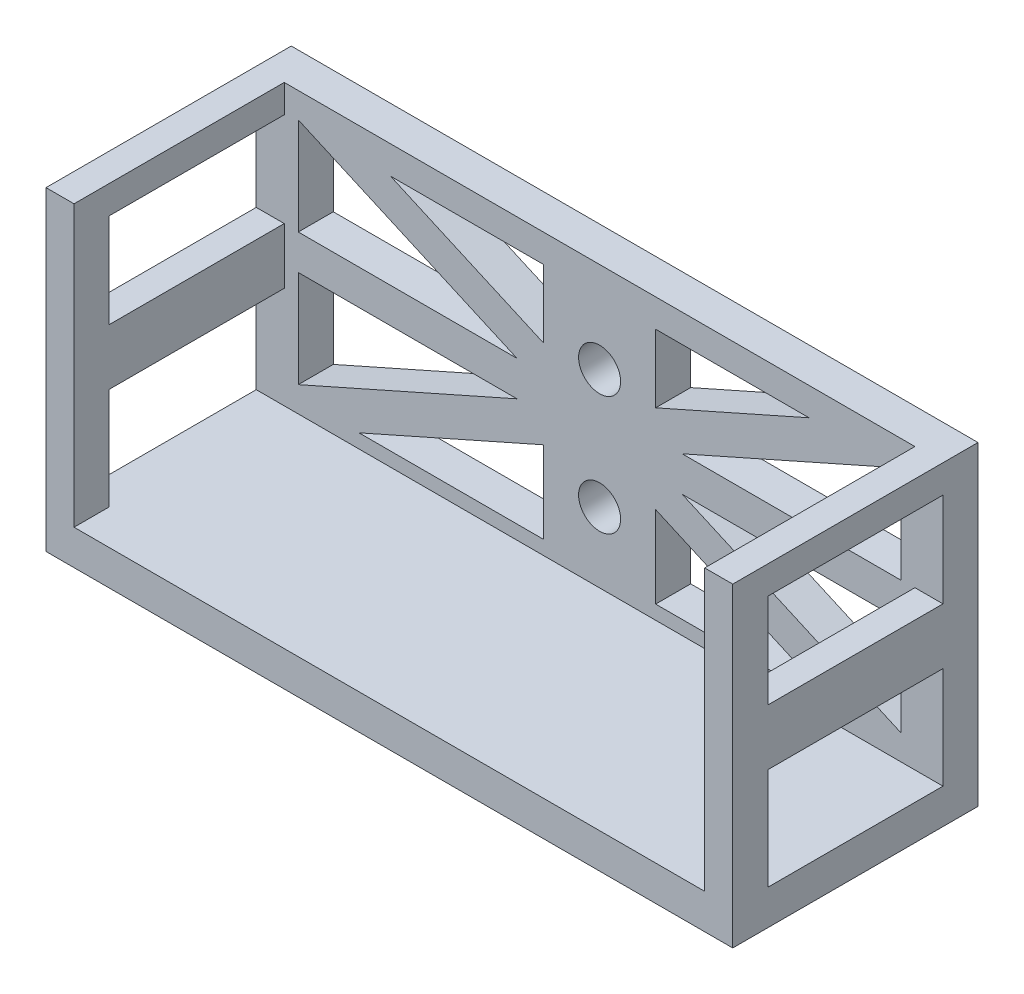
SolidWorks part; units mm, degrees
material "6061-T6 (SS)"
ref_plane "Front Plane" through (0, 0, 0) normal (0, 0, 1) x (1, 0, 0)
ref_plane "Top Plane" through (0, 0, 0) normal (0, 1, 0) x (1, 0, 0)
ref_plane "Right Plane" through (0, 0, 0) normal (1, 0, 0) x (0, 0, -1)
sketch "Sketch1" plane through (0, 0, 0) normal (0, 0, 1) x (1, 0, 0)
  line L1 (-45, 20) -> (45, 20)
  line L2 (-45, 20) -> (-45, -20)
  line L3 (-45, -20) -> (45, -20)
  line L4 (45, 20) -> (45, -20)
  line L5 (-45, 20) -> (45, -20) construction
  line L6 (-45, -20) -> (45, 20) construction
  point P0 (0, 0)
  dimension "D1" = 40
  dimension "D2" = 90
extrude "Boss-Extrude1" add sketch "Sketch1" along normal blind 5
sketch "Sketch2" plane through (0, 0, 0) normal (0, 0, 1) x (1, 0, 0)
  line L1 (-45, 20) -> (-49, 20)
  line L2 (-45, 20) -> (-45, -19.9715)
  line L4 (-49, 20) -> (-49, -19.9715)
  line L5 (45, 20) -> (49, 20)
  line L6 (45, 20) -> (45, -19.9715)
  line L8 (49, 20) -> (49, -19.9715)
  line L9 (-45, -19.9715) -> (45, -19.9715)
  line L10 (-49, -19.9715) -> (-49, -24.9715)
  line L11 (-49, -24.9715) -> (49, -24.9715)
  line L12 (49, -19.9715) -> (49, -24.9715)
  dimension "D1" = 4
  dimension "D2" = 4
  dimension "D3" = 5
extrude "Boss-Extrude2" add sketch "Sketch2" along normal blind 35
sketch "Sketch3" plane through (0, 0, 5) normal (0, 0, 1) x (1, 0, 0)
  line L0 (0, 20) -> (0, -24.9715) construction
  line L1 (45, 20) -> (-45, 20) construction
  line L2 (-49, -24.9715) -> (49, -24.9715) construction
  line L3 (-45, -19.9715) -> (45, -19.9715) construction
  circle A0 centre (0, 7.0285) radius 3
  circle A1 centre (0, -9.9715) radius 3
  dimension "D1" = 6
  dimension "D2" = 6
  dimension "D3" = 17
  dimension "D4" = 10
extrude "Cut-Extrude1" cut sketch "Sketch3" against normal through all
sketch "Sketch4" plane through (0, 0, 5) normal (0, 0, 1) x (1, 0, 0)
  line L0 (-45, 20) -> (0, 0) construction
  line L1 (0, 0) -> (45, -19.9715) construction
  line L2 (45, -19.9715) -> (45, 20) construction
  line L3 (45, 20) -> (0, 0) construction
  line L4 (0, 0) -> (-45, -19.9715) construction
  line L5 (-45, -19.9715) -> (-45, 0.0142) construction
  line L6 (-45, -19.9715) -> (-45, 20) construction
  line L7 (-45, 0.0142) -> (0, 0) construction
  line L8 (0, 0) -> (45, 0.0142) construction
  line L9 (45, -19.9715) -> (-45, -19.9715) construction
  line L11 (-8, 16) -> (-8, 6.2913)
  line L13 (8, 16) -> (8, 6.2856)
  line L14 (-8, 19.9715) -> (8, -19.9715) construction
  line L15 (-8, -19.9715) -> (8, 19.9715) construction
  line L16 (-29.8445, 16) -> (-8, 6.2913)
  line L17 (45, 20) -> (-45, 20) construction
  line L18 (-43, 16.3753) -> (-11.7889, 2.5037)
  line L19 (-43, -16.3487) -> (-11.7875, -2.4963)
  line L20 (-34.3307, -17.9715) -> (-8, -6.2856)
  line L21 (-43, 2.5136) -> (-11.7889, 2.5037)
  line L22 (-43, -2.4864) -> (-11.7875, -2.4963)
  line L23 (-43, 16.3753) -> (-43, 2.5136)
  line L24 (-29.8445, 16) -> (-8, 16)
  line L25 (43, 16.3487) -> (43, 2.4864)
  line L26 (-34.3307, -17.9715) -> (-8, -17.9715)
  line L27 (-45, 20) -> (-45, -19.9715) construction
  line L28 (8, -6.2913) -> (34.2804, -17.9715)
  line L29 (11.7889, -2.5037) -> (43, -16.3753)
  line L30 (11.7875, 2.4963) -> (43, 16.3487)
  line L31 (11.7875, 2.4963) -> (43, 2.4864)
  line L32 (-6.1592, 0.0016) -> (-6.1585, 0.0019)
  line L33 (-8, -6.2856) -> (-8, -17.9715)
  line L34 (-6.1599, 0.0019) -> (-6.1592, 0.0016)
  line L35 (6.1592, -0.0016) -> (6.1673, 0.002)
  line L36 (11.7889, -2.5037) -> (43, -2.513)
  line L37 (6.1512, 0.0019) -> (6.1592, -0.0016)
  line L38 (8, 6.2856) -> (29.8885, 16)
  line L39 (8, -6.2913) -> (8, -17.9715)
  line L40 (8, 16) -> (29.8885, 16)
  line L41 (8, -17.9715) -> (34.2804, -17.9715)
  line L42 (-43, -2.4864) -> (-43, -16.3487)
  line L43 (43, -2.513) -> (43, -16.3753)
  dimension "D1" = 16
  dimension "D2" = 2.5
  dimension "D3" = 2.5
  dimension "D4" = 2.5
  dimension "D5" = 2.5
  dimension "D6" = 2.5
  dimension "D7" = 2.5
  dimension "D8" = 2
  dimension "D9" = 2
  dimension "D10" = 4
  dimension "D11" = 2
extrude "Cut-Extrude2" cut sketch "Sketch4" against normal blind 35 contours L24 L16 L11 | L18 L23 L21 | L22 L42 L19 | L33 L20 L26 | L39 L41 L28 | L43 L36 L29 | L30 L31 L25 | L40 L13 L38
sketch "Sketch5" plane through (49, 0, 0) normal (1, 0, 0) x (0, 0, -1)
  line L0 (-17.5, 20) -> (-17.5, -24.9715) construction
  line L1 (-35, 20) -> (0, 20) construction
  line L2 (-35, -24.9715) -> (0, -24.9715) construction
  line L3 (0, 24.7343) -> (0, -24.7343) construction
  line L4 (-30, 16) -> (-5, 16)
  line L5 (-30, 16) -> (-30, 2.5572)
  line L6 (-30, 2.5572) -> (-5, 2.5572)
  line L7 (-5, 16) -> (-5, 2.5572)
  line L8 (-30, 16) -> (-5, 2.5572) construction
  line L9 (-30, 2.5572) -> (-5, 16) construction
  line L10 (-30, -5.4428) -> (-5, -5.4428)
  line L11 (-30, -5.4428) -> (-30, -19.9715)
  line L12 (-30, -19.9715) -> (-5, -19.9715)
  line L13 (-5, -5.4428) -> (-5, -19.9715)
  line L14 (-30, -5.4428) -> (-5, -19.9715) construction
  line L15 (-30, -19.9715) -> (-5, -5.4428) construction
  point P6 (-17.5, 9.2786)
  point P11 (-17.5, -12.7072)
  dimension "D1" = 4
  dimension "D2" = 5
  dimension "D3" = 5
  dimension "D4" = 5
  dimension "D5" = 8
extrude "Cut-Extrude3" cut sketch "Sketch5" against normal through all both and the other way through all
